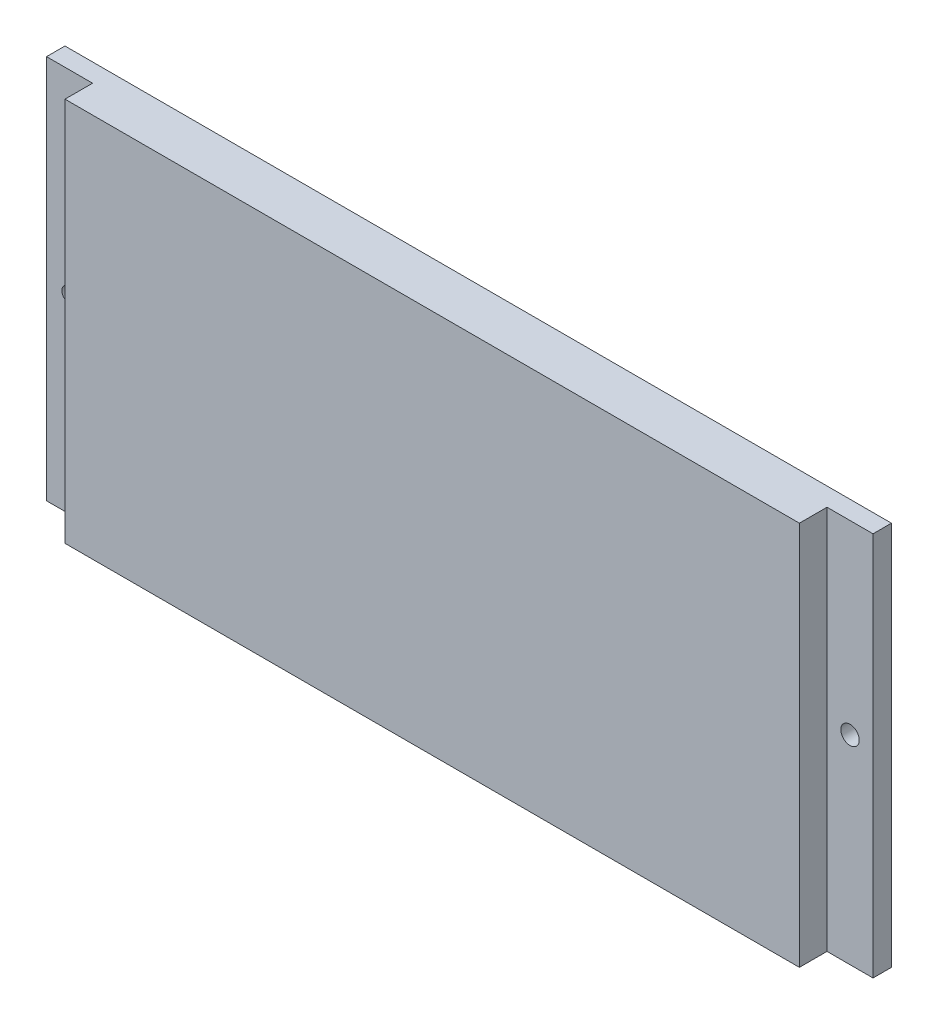
SolidWorks part; units mm, degrees
ref_plane "Front Plane" through (0, 0, 0) normal (0, 0, 1) x (1, 0, 0)
ref_plane "Top Plane" through (0, 0, 0) normal (0, 1, 0) x (1, 0, 0)
ref_plane "Right Plane" through (0, 0, 0) normal (1, 0, 0) x (0, 0, -1)
sketch "Sketch1" plane through (0, 0, 0) normal (0, 0, 1) x (1, 0, 0)
  line L1 (-31.8583, 20.1732) -> (47.9417, 20.1732)
  line L2 (-31.8583, 20.1732) -> (-31.8583, -21.6268)
  line L3 (-31.8583, -21.6268) -> (47.9417, -21.6268)
  line L4 (47.9417, 20.1732) -> (47.9417, -21.6268)
  dimension "D1" = 41.8
  dimension "D2" = 79.8
extrude "Boss-Extrude1" add sketch "Sketch1" along normal blind 3
sketch "Sketch2" plane through (0, 0, 0) normal (0, 0, -1) x (-1, 0, 0)
  line L0 (-52.9417, 20.1732) -> (36.8583, 20.1732)
  line L2 (-52.9417, 20.1732) -> (-52.9417, -21.6268)
  line L4 (31.8583, -21.6268) -> (31.8583, 20.1732)
  line L5 (31.8583, 20.1732) -> (-47.9417, 20.1732)
  line L6 (-47.9417, 20.1732) -> (-47.9417, -21.6268)
  line L7 (-47.9417, -21.6268) -> (31.8583, -21.6268)
  line L8 (31.8583, -21.6268) -> (31.8583, 20.1732)
  line L9 (31.8583, 20.1732) -> (-47.9417, 20.1732)
  line L10 (-47.9417, 20.1732) -> (-47.9417, -21.6268)
  line L11 (-47.9417, -21.6268) -> (31.8583, -21.6268)
  line L12 (36.8583, 20.1732) -> (36.8583, -21.6268)
  line L13 (-52.9417, -21.6268) -> (36.8583, -21.6268)
  dimension "D2" = 5
  dimension "D4" = 5
  dimension "D1" = 0
extrude "Boss-Extrude4" add sketch "Sketch2" along normal blind 2 contours L0 L12 L13 L2
sketch "Sketch3" plane through (0, 0, -2) normal (0, 0, -1) x (-1, 0, 0)
  line L0 (-52.9417, 20.1732) -> (-52.9417, -21.6268) construction
  line L1 (36.8583, 20.1732) -> (36.8583, -21.6268) construction
  circle A0 centre (-50.4417, 0) radius 1
  circle A1 centre (34.3583, -1) radius 0.8339
  dimension "D1" = 2.5
  dimension "D2" = 2.5
extrude "Cut-Extrude1" cut sketch "Sketch3" against normal blind 2
